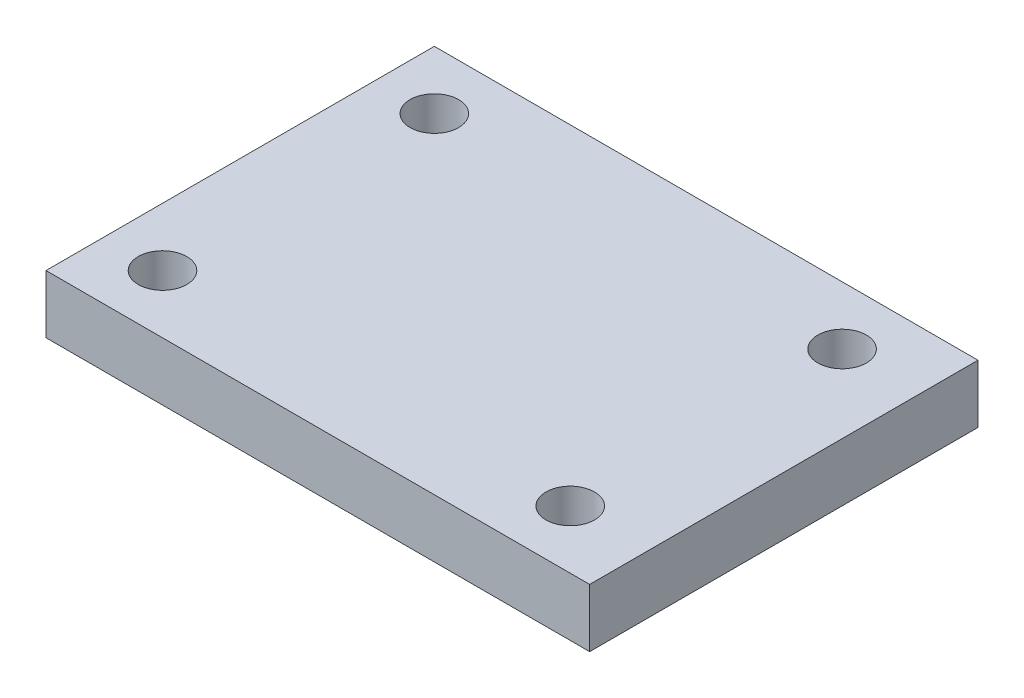
SolidWorks part; units mm, degrees
ref_plane "Front Plane" through (0, 0, 0) normal (0, 0, 1) x (1, 0, 0)
ref_plane "Top Plane" through (0, 0, 0) normal (0, 1, 0) x (1, 0, 0)
ref_plane "Right Plane" through (0, 0, 0) normal (1, 0, 0) x (0, 0, -1)
sketch "Sketch1" plane through (0, 0, 0) normal (0, 1, 0) x (1, 0, 0)
  line L1 (-14, 10) -> (14, 10)
  line L2 (-14, 10) -> (-14, -10)
  line L3 (-14, -10) -> (14, -10)
  line L4 (14, 10) -> (14, -10)
  line L5 (-14, 10) -> (14, -10) construction
  line L6 (-14, -10) -> (14, 10) construction
  point P0 (0, 0)
  dimension "D1" = 20
  dimension "D2" = 28
extrude "Boss-Extrude1" add sketch "Sketch1" along normal blind 3
hole_wizard "M3 Tapped Hole1" positions "Sketch3" profile "Sketch2" tap size "M3" standard "DIN" end condition through all
sketch "Sketch3" plane through (0, 3, 0) normal (0, 1, 0) x (1, 0, 0)
  line L0 (-14, 10) -> (-14, -10) construction
  line L1 (14, 10) -> (-14, 10) construction
  point P0 (-11, 7)
  point P2 (-11, -7)
  point P4 (10, -7)
  point P6 (10, 7)
  dimension "D1" = 14
  dimension "D2" = 21
  dimension "D3" = 3
  dimension "D4" = 3
sketch "Sketch2" plane through (-11, 3, -7) normal (1, 0, 0) x (0, 0, 1)
  line L0 (0, 0) -> (0, 3)
  line L1 (0, 3) -> (1.25, 3)
  line L2 (1.25, 3) -> (1.25, 0)
  line L5 (1.25, 0) -> (0, 0)
  line L11 (0, -6.35) -> (0, 107.95) construction
  dimension "Thru Tap Drill Dia." = 2.5
  dimension "Thru Tap Drill Depth" = 3
cosmetic thread "Hole Thread1" parameters "D2"=3
cosmetic thread "Hole Thread2" parameters "D2"=3
cosmetic thread "Hole Thread3" parameters "D2"=3
cosmetic thread "Hole Thread4" parameters "D2"=3
